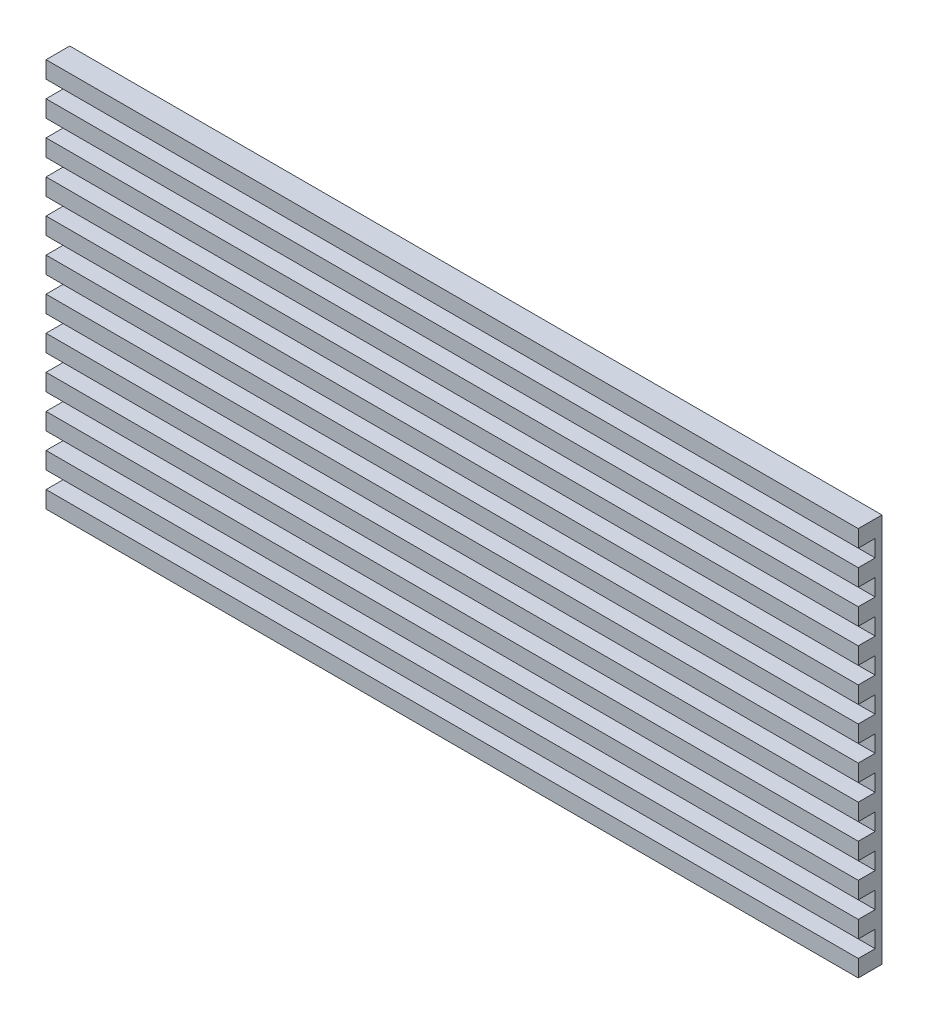
SolidWorks part; units mm, degrees
material "Клен"
ref_plane "Спереди" through (0, 0, 0) normal (0, 0, 1) x (1, 0, 0)
ref_plane "Сверху" through (0, 0, 0) normal (0, 1, 0) x (1, 0, 0)
ref_plane "Справа" through (0, 0, 0) normal (1, 0, 0) x (0, 0, -1)
sketch "Эскиз1" plane through (0, 0, 0) normal (0, 0, 1) x (1, 0, 0)
  line L1 (0, 0) -> (2400, 0)
  line L2 (0, 0) -> (0, 1150)
  line L3 (0, 1150) -> (2400, 1150)
  line L4 (2400, 0) -> (2400, 1150)
  dimension "D1" = 1150
  dimension "D2" = 2400
extrude "Бобышка-Вытянуть1" add sketch "Эскиз1" along normal blind 20
sketch "Эскиз2" plane through (0, 0, 20) normal (0, 0, 1) x (1, 0, 0)
  line L0 (2400, 0) -> (2400, 1150) construction
  line L1 (0, 1150) -> (2400, 1150)
  line L2 (0, 1150) -> (0, 1100)
  line L3 (0, 1100) -> (2400, 1100)
  line L4 (2400, 1150) -> (2400, 1100)
  dimension "D1" = 50
extrude "Бобышка-Вытянуть2" add sketch "Эскиз2" along normal blind 50
pattern_linear "Линейный массив1" count 12 spacing 100 along (0, -1, 0) of "Бобышка-Вытянуть2"
equation "\"D1@Бобышка-Вытянуть2\"=\"D1@Эскиз2\""
